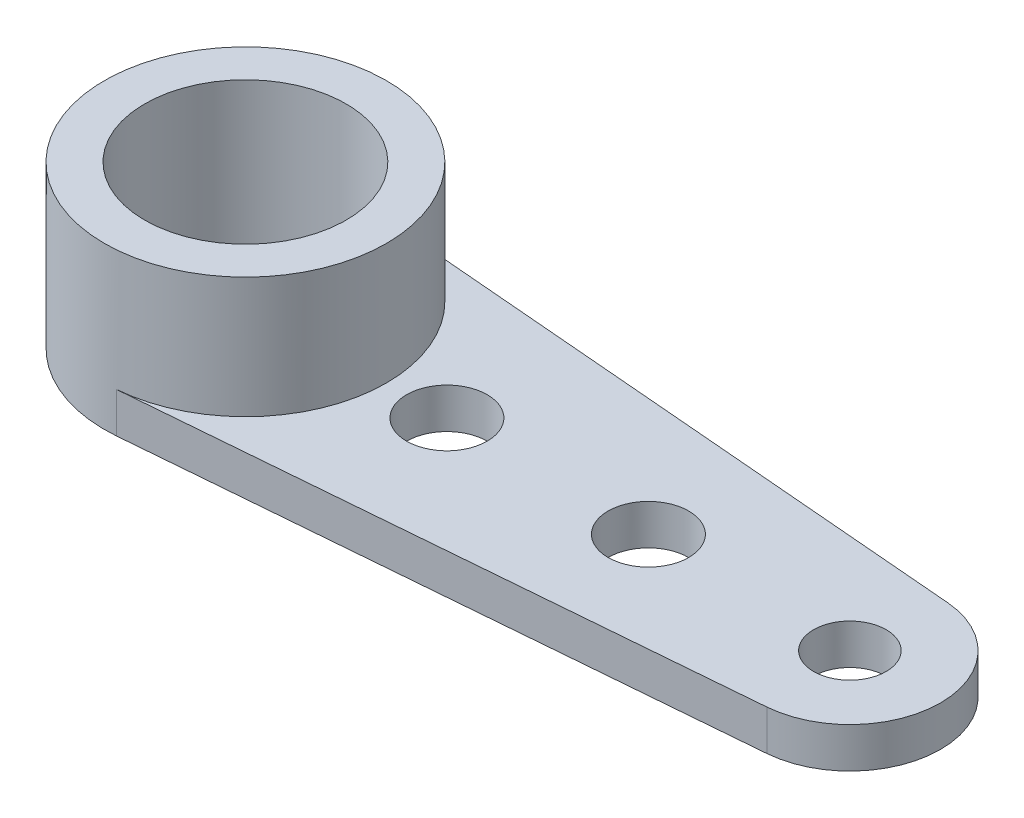
SolidWorks part; units mm, degrees
material "6061-T6 (SS)"
ref_plane "Front Plane" through (0, 0, 0) normal (0, 0, 1) x (1, 0, 0)
ref_plane "Top Plane" through (0, 0, 0) normal (0, 1, 0) x (1, 0, 0)
ref_plane "Right Plane" through (0, 0, 0) normal (1, 0, 0) x (0, 0, -1)
sketch "Sketch1" plane through (0, 0, 0) normal (0, 1, 0) x (1, 0, 0)
  line L0 (0.2917, 3.4878) -> (15.1875, 2.2422)
  line L1 (0.2917, -3.4878) -> (15.1875, -2.2422)
  circle A0 centre (0, 0) radius 3.5
  circle A1 centre (15, 0) radius 2.25
  dimension "D2" = 7
  dimension "D3" = 4.5
  dimension "D1" = 15
extrude "Boss-Extrude1" add sketch "Sketch1" along normal blind 1 contours A1 L0 A0 L1 | A0 | A1 L0
sketch "Sketch2" plane through (0, 1, 0) normal (0, 1, 0) x (1, 0, 0)
  circle A0 centre (0, 0) radius 3.5
extrude "Boss-Extrude2" add sketch "Sketch2" along normal blind 3
sketch "Sketch3" plane through (0, 4, 0) normal (0, 1, 0) x (1, 0, 0)
  circle A0 centre (0, 0) radius 2.5
  dimension "D1" = 5
extrude "Cut-Extrude1" cut sketch "Sketch3" against normal through all
sketch "Sketch4" plane through (0, 0, 0) normal (0, -1, 0) x (1, 0, 0)
  circle A0 centre (15, 0) radius 0.9
  dimension "D1" = 1.8
extrude "Cut-Extrude2" cut sketch "Sketch4" against normal through all
sketch "Sketch5" plane through (0, 0, 0) normal (0, -1, 0) x (1, 0, 0)
  line L0 (0, 0) -> (15, 0)
  circle A0 centre (5, 0) radius 1
  circle A1 centre (10, 0) radius 1
  dimension "D3" = 2
  dimension "D4" = 2
  dimension "D1" = 5
  dimension "D2" = 5
extrude "Cut-Extrude3" cut sketch "Sketch5" against normal through all contours L0 A0 | L0 A0 | L0 A1 | L0 A1
